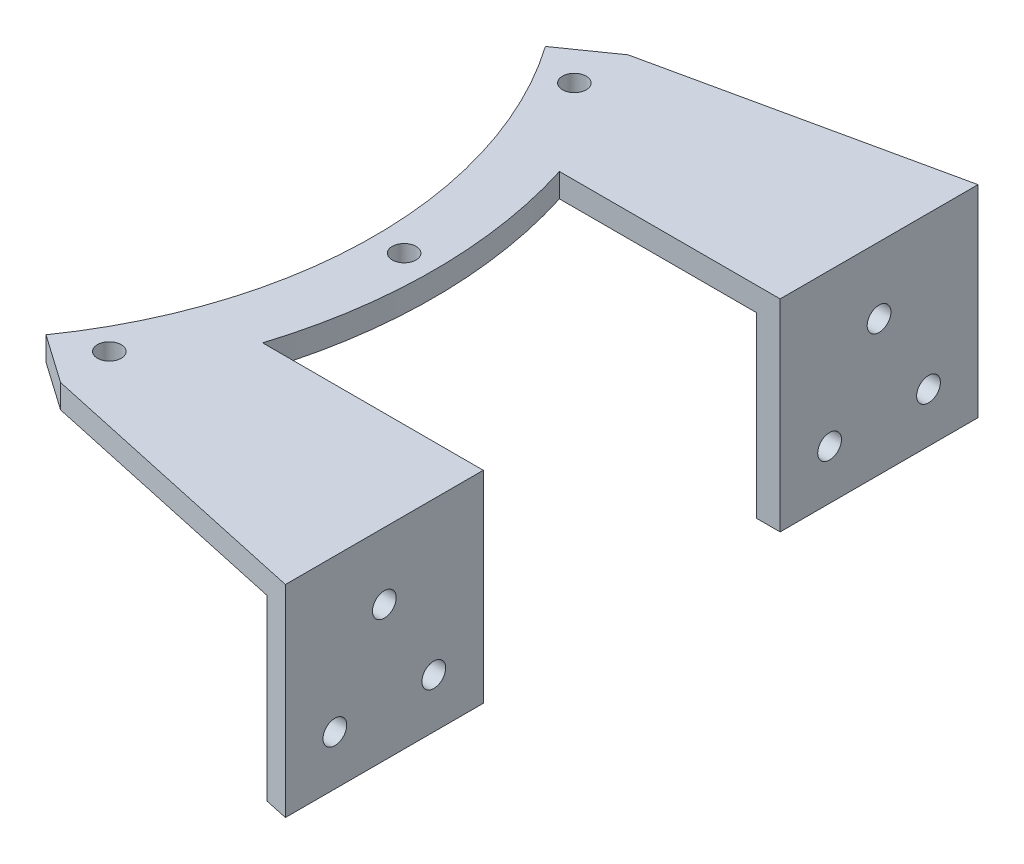
SolidWorks part; units mm, degrees
ref_plane "Front Plane" through (0, 0, 0) normal (0, 0, 1) x (1, 0, 0)
ref_plane "Top Plane" through (0, 0, 0) normal (0, 1, 0) x (1, 0, 0)
ref_plane "Right Plane" through (0, 0, 0) normal (1, 0, 0) x (0, 0, -1)
sketch "Sketch1" plane through (0, 0, 0) normal (0, 1, 0) x (1, 0, 0)
  line L0 (0, 0) -> (250, 0) construction
  line L1 (0, 0) -> (216.5064, 125) construction
  line L2 (0, 0) -> (216.5064, -125) construction
  line L3 (216.5064, 125) -> (216.5064, -125) construction
  line L5 (204.788, 143.3941) -> (204.788, -143.3941) construction
  line L11 (350, 175) -> (350, 75)
  line L12 (350, 75) -> (238.4848, 75)
  line L13 (350, -175) -> (350, -75)
  line L14 (350, -75) -> (238.4848, -75)
  line L15 (0, 0) -> (204.788, 143.3941) construction
  line L16 (0, 0) -> (204.788, -143.3941) construction
  line L17 (180.2134, 126.1868) -> (204.788, 143.3941)
  line L18 (180.2134, -126.1868) -> (204.788, -143.3941)
  line L21 (204.788, 143.3941) -> (350, 175)
  line L22 (204.788, -143.3941) -> (350, -175)
  arc A0 (180.2134, -126.1868) -> (180.2134, 126.1868) centre (0, 0) ccw
  arc A1 (204.788, -143.3941) -> (204.788, 143.3941) centre (0, 0) ccw construction
  circle A2 centre (0, 0) radius 235 construction
  circle A3 centre (203.516, -117.5) radius 6
  circle A4 centre (235, 0) radius 6
  circle A5 centre (203.516, 117.5) radius 6
  arc A8 (238.4848, -75) -> (238.4848, 75) centre (0, 0) ccw
  dimension "D11" = 250
  dimension "D2" = 220
  dimension "D4" = 470
  dimension "D5" = 12
  dimension "D3" = 60
  dimension "D6" = 100
  dimension "D7" = 100
  dimension "D8" = 350
  dimension "D9" = 70
  dimension "D10" = 350
extrude "Boss-Extrude2" add sketch "Sketch1" along normal blind 12
sketch "Sketch2" plane through (0, 0, 0) normal (0, -1, 0) x (-1, 0, 0)
  line L0 (-350, -175) -> (-350, -75)
  line L1 (-350, -75) -> (-338, -75)
  line L2 (-350, -75) -> (-238.4848, -75) construction
  line L3 (-338, -75) -> (-338, -172.3882)
  line L4 (-204.788, -143.3941) -> (-350, -175) construction
  line L5 (-338, -172.3882) -> (-350, -175)
  line L6 (-350, 75) -> (-350, 175)
  line L7 (-350, 175) -> (-338, 172.3882)
  line L8 (-350, 175) -> (-204.788, 143.3941) construction
  line L9 (-338, 172.3882) -> (-338, 75)
  line L10 (-238.4848, 75) -> (-350, 75) construction
  line L11 (-338, 75) -> (-350, 75)
  dimension "D1" = 12
extrude "Boss-Extrude3" add sketch "Sketch2" along normal blind 90
sketch "Sketch4" plane through (338, 0, 0) normal (-1, 0, 0) x (0, 0, 1)
  line L0 (-60, -65) -> (-158.8275, -65) construction
  line L3 (0, 0) -> (0, -141.9458) construction
  circle A0 centre (-150, -65) radius 6
  circle A1 centre (-100, -65) radius 6
  circle A2 centre (-125, -21.6987) radius 6
  circle A3 centre (150, -65) radius 6
  circle A4 centre (125, -21.6987) radius 6
  circle A5 centre (100, -65) radius 6
  dimension "D5" = 12
  dimension "D1" = 65
  dimension "D2" = 50
  dimension "D3" = 50
  dimension "D4" = 50
  dimension "D6" = 150
extrude "Cut-Extrude1" cut sketch "Sketch4" against normal through all
equation "\"mbtOD\" = 850"
equation "\"mbtT\" = 6"
equation "\"mbtL\" = 1500"
equation "\"mbtFlangeOD\" = 950"
equation "\"mbtFlangeT\" = 12"
equation "\"mbtFlangeBoltCircleDia\" = 650"
equation "\"mbtFlangeHoleDia\" = 12"
equation "\"mbtOringSize\" = 10 "
equation "\"mbtOringDia\" = 620"
equation "\"mbtWidth\" = 2250"
equation "\"skiWidth\" = 1250"
equation "\"mbtCapL\" = 500"
equation "\"vbtRearOD\" = 500"
equation "\"vbtRearT\" = 6.25"
equation "\"vbtRearFlangeOD\" = 600"
equation "\"vbtRearFlangeT\" = 12"
equation "\"vbtRearBoltHoleDia\" = 12"
equation "\"vbtFrontOD\" = 440"
equation "\"vbtFrontT\" = 25"
equation "\"vbtFrontFlangeOD\" = 500"
equation "\"vbtFrontFlangeT\" = 12"
equation "\"vbtFrontBoltHoleDia\" = 12"
equation "\"D8@Sketch1\"=\"vbtFrontFlangeOD\"/2+100mm"
equation "\"D1@Boss-Extrude2\"=\"vbtRearFlangeT\""
equation "\"D11@Sketch1\"=\"vbtFrontFlangeOD\"/2"
equation "\"D2@Sketch1\"=\"vbtFrontOD\"/2"
equation "\"D4@Sketch1\"=(\"vbtFrontOD\"+\"vbtFrontFlangeOD\")/2"
equation "\"D5@Sketch1\"=\"vbtFrontBoltHoleDia\""
equation "\"D1@Sketch2\"=\"vbtFrontFlangeT\""
